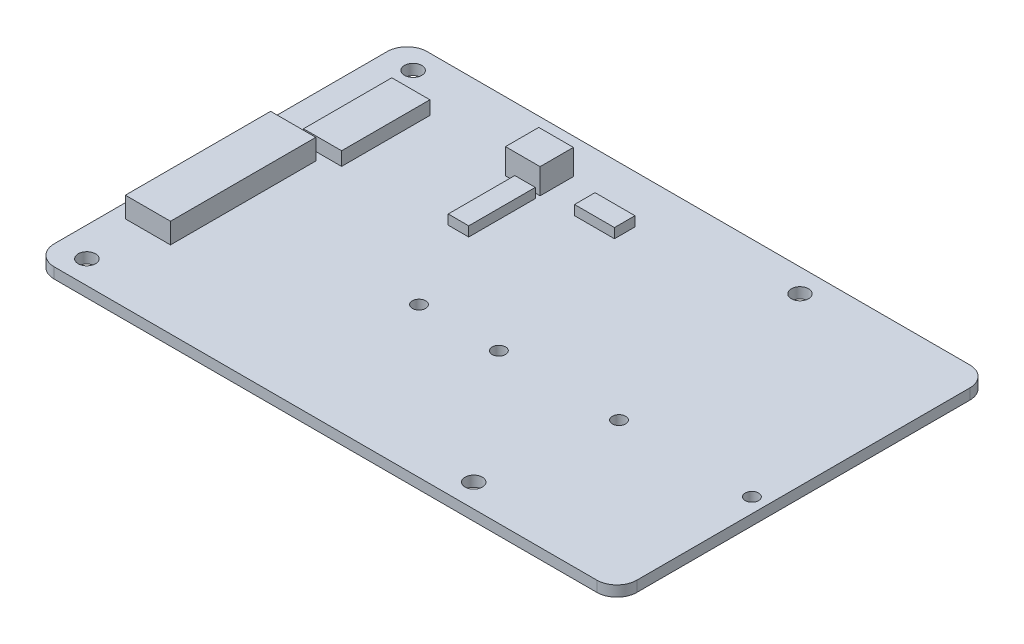
SolidWorks part; units mm, degrees
ref_plane "Front Plane" through (0, 0, 0) normal (0, 0, 1) x (1, 0, 0)
ref_plane "Top Plane" through (0, 0, 0) normal (0, 1, 0) x (1, 0, 0)
ref_plane "Right Plane" through (0, 0, 0) normal (1, 0, 0) x (0, 0, -1)
sketch "Sketch1" plane through (0, 0, 0) normal (0, 1, 0) x (1, 0, 0)
  line L0 (-883.8335, 356.6129) -> (-766.7994, 356.6129) construction
  line L1 (-887.6646, 305.0129) -> (-747.2497, 305.0129) construction
  line L2 (-870.6354, 358.8129) -> (-789.1354, 358.8129)
  line L3 (-873.6354, 355.8129) -> (-873.6354, 305.8129)
  line L4 (-870.6354, 302.8129) -> (-789.1354, 302.8129)
  line L5 (-786.1354, 355.8129) -> (-786.1354, 305.8129)
  line L6 (-870.5354, 364.6916) -> (-870.5354, 297.5366) construction
  line L7 (-809.8354, 368.0031) -> (-809.8354, 291.7556) construction
  circle A0 centre (-869.2354, 355.3129) radius 1.3
  circle A1 centre (-869.2354, 306.3129) radius 1.3
  circle A2 centre (-811.1354, 355.3129) radius 1.3
  circle A3 centre (-811.1354, 306.3129) radius 1.3
  arc A4 (-873.6354, 305.8129) -> (-870.6354, 302.8129) centre (-870.6354, 305.8129) ccw
  arc A5 (-789.1354, 302.8129) -> (-786.1354, 305.8129) centre (-789.1354, 305.8129) ccw
  arc A6 (-789.1354, 358.8129) -> (-786.1354, 355.8129) centre (-789.1354, 355.8129) cw
  arc A7 (-870.6354, 358.8129) -> (-873.6354, 355.8129) centre (-870.6354, 355.8129) ccw
  point P24 (-786.1354, 302.8129)
  point P27 (-786.1354, 358.8129)
  point P30 (-873.6354, 358.8129)
  dimension "D7" = 2.6
  dimension "D8" = 3
  dimension "D1" = 87.5
  dimension "D2" = 56
  dimension "D3" = 2.2
  dimension "D4" = 2.2
  dimension "D5" = 3.1
  dimension "D6" = 23.7
extrude "pcb" add sketch "Sketch1" along normal blind 1.6
sketch "Sketch2" plane through (0, 1.6, 0) normal (0, 1, 0) x (1, 0, 0)
  line L0 (-879.9669, 324.2929) -> (-782.0982, 324.2929) construction
  line L1 (-870.6354, 302.8129) -> (-789.1354, 302.8129) construction
  line L2 (-787.3354, 361.5898) -> (-787.3354, 295.8429) construction
  line L3 (-786.1354, 305.8129) -> (-786.1354, 355.8129) construction
  circle A0 centre (-788.3354, 325.2929) radius 1
  circle A1 centre (-808.2954, 325.2929) radius 1
  circle A2 centre (-826.3354, 325.2929) radius 1
  circle A3 centre (-838.3354, 325.2929) radius 1
  dimension "D3" = 2
  dimension "D4" = 17.96
  dimension "D5" = 16.04
  dimension "D6" = 10
  dimension "D1" = 21.48
  dimension "D2" = 1.2
extrude "NVMe-M-Key screw holes" cut sketch "Sketch2" against normal up to next
sketch "Sketch3" plane through (0, 1.6, 0) normal (0, 1, 0) x (1, 0, 0)
  line L0 (-879.2816, 314.3929) -> (-776.3794, 314.3929) construction
  line L1 (-871.5354, 363.533) -> (-871.5354, 296.8284) construction
  line L2 (-870.6354, 302.8129) -> (-789.1354, 302.8129) construction
  line L3 (-873.6354, 355.8129) -> (-873.6354, 305.8129) construction
  line L5 (-871.5354, 314.3929) -> (-864.7554, 314.3929)
  line L6 (-871.5354, 314.3929) -> (-871.5354, 336.2129)
  line L7 (-871.5354, 336.2129) -> (-864.7554, 336.2129)
  line L8 (-864.7554, 314.3929) -> (-864.7554, 336.2129)
  dimension "D1" = 11.58
  dimension "D2" = 2.1
  dimension "D3" = 6.78
  dimension "D4" = 21.82
extrude "NVMe-M-Key connector" add sketch "Sketch3" along normal blind 3.08
sketch "Sketch4" plane through (0, 1.6, 0) normal (0, 1, 0) x (1, 0, 0)
  line L0 (-867.8354, 363.533) -> (-867.8354, 296.8284) construction
  line L1 (-876.4205, 337.4518) -> (-773.2022, 337.4518) construction
  line L2 (-873.6354, 355.8129) -> (-873.6354, 305.8129) construction
  line L3 (-867.8354, 337.4518) -> (-862.1154, 337.4518)
  line L4 (-867.8354, 337.4518) -> (-867.8354, 350.7118)
  line L5 (-867.8354, 350.7118) -> (-862.1154, 350.7118)
  line L6 (-862.1154, 337.4518) -> (-862.1154, 350.7118)
  dimension "D1" = 13.26
  dimension "D2" = 5.72
  dimension "D3" = 5.8
extrude "PCI-E connector" add sketch "Sketch4" along normal blind 2.04
sketch "Sketch5" plane through (0, 1.6, 0) normal (0, 1, 0) x (1, 0, 0)
  line L0 (-848.5854, 362.4265) -> (-848.5854, 297.2235) construction
  line L1 (-878.8864, 353.5329) -> (-772.2697, 353.5329) construction
  line L2 (-873.6354, 355.8129) -> (-873.6354, 305.8129) construction
  line L3 (-789.1354, 358.8129) -> (-870.6354, 358.8129) construction
  line L5 (-848.5854, 353.5329) -> (-843.3854, 353.5329)
  line L6 (-848.5854, 353.5329) -> (-848.5854, 348.5329)
  line L7 (-848.5854, 348.5329) -> (-843.3854, 348.5329)
  line L8 (-843.3854, 353.5329) -> (-843.3854, 348.5329)
  dimension "D1" = 25.05
  dimension "D2" = 5.28
  dimension "D3" = 5.2
  dimension "D4" = 5
extrude "Inductance" add sketch "Sketch5" along normal blind 3.8
sketch "Sketch6" plane through (0, 1.6, 0) normal (0, 1, 0) x (1, 0, 0)
  line L0 (-843.3854, 348.5329) -> (-843.3854, 299.3939) construction
  line L1 (-883.4549, 337.8129) -> (-780.0277, 337.8129) construction
  line L2 (-789.1354, 358.8129) -> (-870.6354, 358.8129) construction
  line L3 (-853.8905, 348.5329) -> (-781.7611, 348.5329) construction
  line L4 (-843.3854, 337.8129) -> (-846.4654, 337.8129)
  line L5 (-843.3854, 337.8129) -> (-843.3854, 347.8129)
  line L6 (-843.3854, 347.8129) -> (-846.4654, 347.8129)
  line L7 (-846.4654, 337.8129) -> (-846.4654, 347.8129)
  line L8 (-832.2154, 364.3971) -> (-832.2154, 299.3939) construction
  line L9 (-873.6354, 355.8129) -> (-873.6354, 305.8129) construction
  line L11 (-832.2154, 348.5329) -> (-838.2154, 348.5329)
  line L12 (-832.2154, 348.5329) -> (-832.2154, 351.6129)
  line L13 (-832.2154, 351.6129) -> (-838.2154, 351.6129)
  line L14 (-838.2154, 348.5329) -> (-838.2154, 351.6129)
  dimension "D1" = 21
  dimension "D2" = 10
  dimension "D3" = 3.08
  dimension "D4" = 41.42
  dimension "D5" = 3.08
  dimension "D6" = 6
extrude "Capacitors" add sketch "Sketch6" along normal blind 1.46
